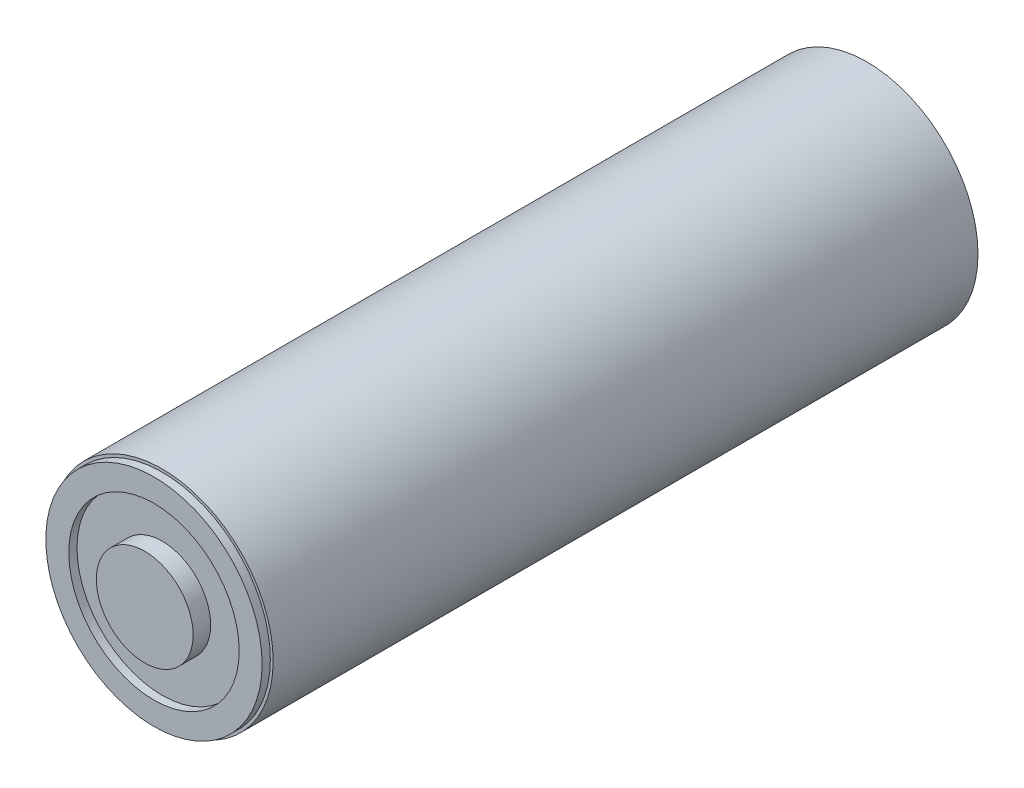
SolidWorks part; units mm, degrees
material "P42A"
ref_plane "X-Y Datum" through (0, 0, 0) normal (0, 0, 1) x (1, 0, 0)
ref_plane "X-Z Datum" through (0, 0, 0) normal (0, 1, 0) x (1, 0, 0)
ref_plane "Y-Z Datum" through (0, 0, 0) normal (1, 0, 0) x (0, 0, -1)
sketch "Sketch1" plane through (0, 0, 0) normal (0, 0, 1) x (1, 0, 0)
  circle A0 centre (0, 0) radius 10.775
  dimension "D1" = 21.55
extrude "Boss-Extrude1" add sketch "Sketch1" along normal blind 68.45
sketch "Sketch2" plane through (0, 0, 68.45) normal (0, 0, 1) x (1, 0, 0)
  circle A0 centre (0, 0) radius 4.7
extrude "Boss-Extrude2" add sketch "Sketch2" along normal blind 1.7
sketch "Sketch3" plane through (0, 0, 68.45) normal (0, 0, 1) x (1, 0, 0)
  circle A2 centre (0, 0) radius 8.275
  circle A3 centre (0, 0) radius 8.275
  circle A4 centre (0, 0) radius 10.5
  dimension "D1" = 2.5
extrude "Boss-Extrude3" add sketch "Sketch3" along normal blind 0.8
